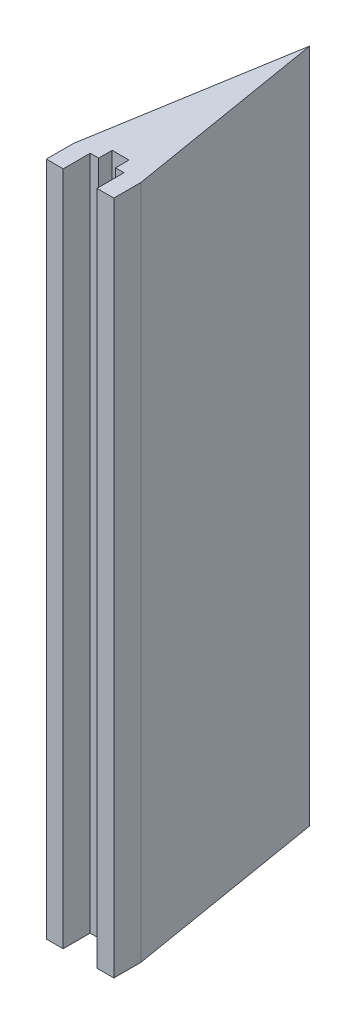
SolidWorks part; units mm, degrees
material "6061-T6 (SS)"
ref_plane "Front Plane" through (0, 0, 0) normal (0, 0, 1) x (1, 0, 0)
ref_plane "Top Plane" through (0, 0, 0) normal (0, 1, 0) x (1, 0, 0)
ref_plane "Right Plane" through (0, 0, 0) normal (1, 0, 0) x (0, 0, -1)
sketch "Sketch1" plane through (0, 0, 0) normal (0, 1, 0) x (1, 0, 0)
  line L0 (0, 0) -> (0, 38.1) construction
  line L1 (0, 38.1) -> (-6.35, 0)
  line L2 (0, 38.1) -> (6.35, 0)
  line L3 (0, 18.7872) -> (3.2182, -0.522) construction
  line L4 (0, 18.7872) -> (-3.2182, -0.522) construction
  line L5 (0, 0) -> (3.175, 0) construction
  line L6 (0, 0) -> (-3.175, 0) construction
  line L7 (-3.175, 0) -> (-3.175, -5.08)
  line L8 (-3.175, -5.08) -> (-6.35, -5.08)
  line L9 (-6.35, -5.08) -> (-6.35, 0)
  line L10 (3.175, 0) -> (3.175, -5.08)
  line L11 (3.175, -5.08) -> (6.35, -5.08)
  line L12 (6.35, -5.08) -> (6.35, 0)
  line L13 (-3.175, 0) -> (-1.5875, 0)
  line L19 (-1.5875, 0) -> (-1.5875, 2.54)
  line L20 (-1.5875, 2.54) -> (1.5875, 2.54)
  line L21 (1.5875, 2.54) -> (1.5875, 0)
  line L22 (1.5875, 0) -> (3.175, 0)
  dimension "D7" = 2.54
  dimension "D1" = 38.1
  dimension "D2" = 6.35
  dimension "D3" = 6.35
  dimension "D5" = 3.175
  dimension "D6" = 3.175
  dimension "D8" = 5.08
  dimension "D9" = 5.08
  dimension "D10" = 3.175
  dimension "D11" = 1.5875
  dimension "D4" = 3.175
extrude "Boss-Extrude1" add sketch "Sketch1" along normal blind 127
